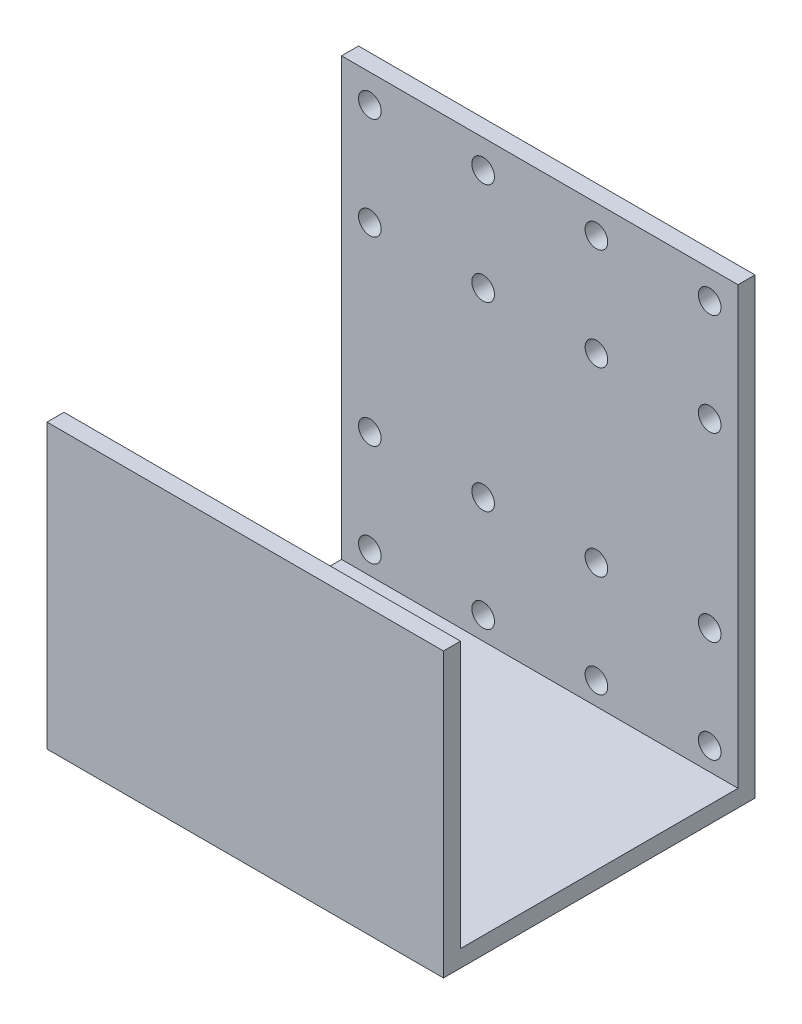
SolidWorks part; units mm, degrees
ref_plane "Front (XY)" through (0, 0, 0) normal (0, 0, 1) x (1, 0, 0)
ref_plane "Top (XZ)" through (0, 0, 0) normal (0, 1, 0) x (1, 0, 0)
ref_plane "Right (YZ)" through (0, 0, 0) normal (1, 0, 0) x (0, 0, -1)
sketch "Sketch1" plane through (0, 0, 0) normal (0, 0, 1) x (1, 0, 0)
  line L0 (-35, 0) -> (35, 0)
  line L1 (35, 0) -> (35, -80)
  line L2 (35, -80) -> (-35, -80)
  line L3 (-35, -80) -> (-35, 0)
  point P2 (0, 0)
  dimension "D1" = 70
  dimension "D2" = 80
extrude "Boss-Extrude1" add sketch "Sketch1" along normal blind 55
sketch "Sketch2" plane through (0, 0, 0) normal (1, 0, 0) x (0, 0, -1)
  line L0 (-55, 0) -> (0, 0) construction
  line L1 (-55, -80) -> (-55, 0) construction
  line L2 (-55, 0) -> (-27.5, 0)
  line L3 (-55, -30) -> (-55, 0)
  line L4 (-27.5, 0) -> (-27.5, -30)
  line L5 (-27.5, -30) -> (-55, -30)
  dimension "D1" = 30
  dimension "D2" = 27.5
extrude "Cut-Extrude1" cut sketch "Sketch2" against normal through all both and the other way through all
shell "Shell1" thickness 3
sketch "Sketch8" plane through (0, -77, 0) normal (0, 1, 0) x (1, 0, 0)
  line L0 (-35, -52) -> (-35, -3) construction
  line L2 (-26.5, -23.45) -> (-35, -23.45)
  line L3 (-26.5, -31.55) -> (-35, -31.55)
  line L4 (-35, -31.55) -> (-35, -23.45)
  arc A0 (-26.5, -31.55) -> (-26.5, -23.45) centre (-26.5, -27.5) ccw
  point P5 (-35, -27.5)
  dimension "D1" = 8.1
  dimension "D2" = 8.5
extrude "Cut-Extrude2" cut sketch "Sketch8" against normal through all
sketch "Sketch9" plane through (0, 0, 3) normal (0, 0, 1) x (1, 0, 0)
  line L0 (35, 0) -> (-35, 0) construction
  line L1 (-35, 0) -> (-35, -77) construction
  circle A0 centre (-30, -5) radius 2
  circle A1 centre (-10, -5) radius 2
  circle A2 centre (-30, -23) radius 2
  circle A3 centre (-10, -23) radius 2
  point P8 (0, 0)
  point P9 (0, 0)
  point P10 (0, 0)
  dimension "D1" = 4
  dimension "D2" = 5
  dimension "D3" = 5
  dimension "D4" = 20
  dimension "D5" = 18
extrude "Cut-Extrude3" cut sketch "Sketch9" against normal through all
pattern_linear "LPattern1" count 2 spacing 40 along (1, 0, 0) count 2 spacing 50 along (0, -1, 0) of "Cut-Extrude3"
